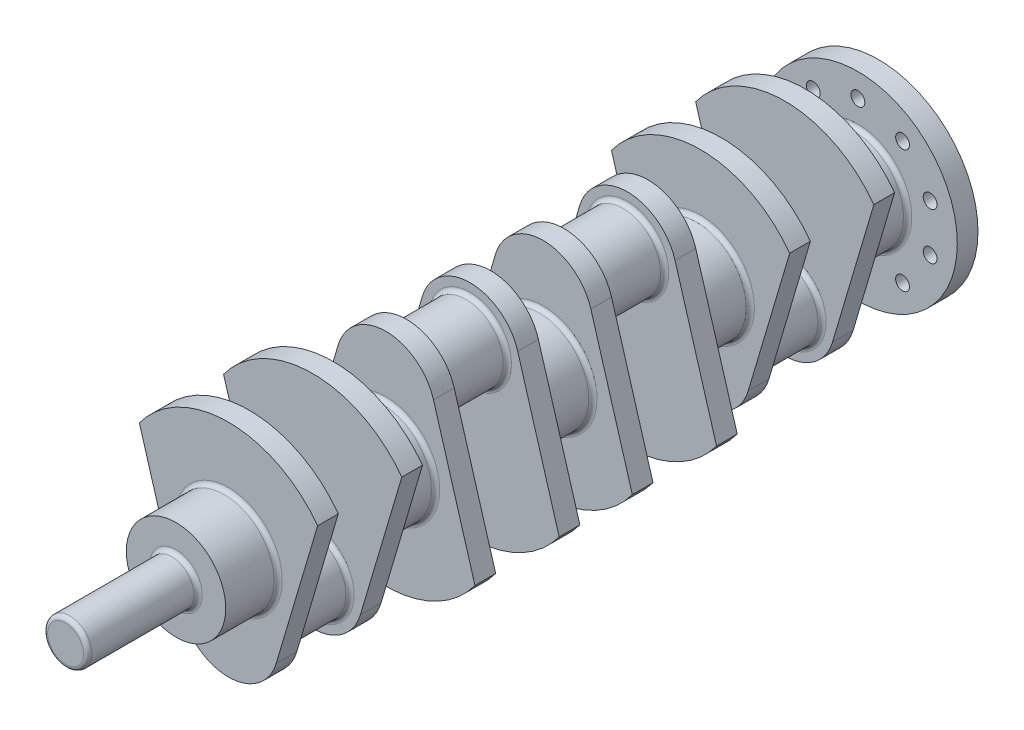
SolidWorks part; units mm, degrees
ref_plane "Front Plane" through (0, 0, 0) normal (0, 0, 1) x (1, 0, 0)
ref_plane "Top Plane" through (0, 0, 0) normal (0, 1, 0) x (1, 0, 0)
ref_plane "Right Plane" through (0, 0, 0) normal (1, 0, 0) x (0, 0, -1)
sketch "Sketch1" plane through (0, 0, 0) normal (0, 0, 1) x (1, 0, 0)
  line L0 (0, 48.3144) -> (0, -83.5014) construction
  line L1 (-46.5551, 0) -> (125.5904, 0) construction
  line L2 (-64.5699, 47.2306) -> (-34.5175, -54.2246)
  line L3 (64.5699, 47.2306) -> (34.5175, -54.2246)
  circle A0 centre (0, -44) radius 36
  arc A1 (-64.5699, 47.2306) -> (64.5699, 47.2306) centre (0, 0) cw
  dimension "D1" = 72
  dimension "D4" = 80
  dimension "D2" = 33
  dimension "D3" = 44
extrude "Boss-Extrude1" add sketch "Sketch1" along normal blind 15 contours A1 L2 A0 L3 | A0
sketch "Sketch2" plane through (0, 0, 15) normal (0, 0, 1) x (1, 0, 0)
  circle A1 centre (0, -44) radius 27
  dimension "D1" = 54
extrude "Boss-Extrude2" add sketch "Sketch2" along normal blind 46
sketch "Sketch3" plane through (0, 0, 0) normal (0, 0, -1) x (-1, 0, 0)
  circle A0 centre (0, 0) radius 36
  dimension "D1" = 72
extrude "Boss-Extrude3" add sketch "Sketch3" along normal blind 38
ref_plane "Plane1" through (0, 0, 38) normal (0, 0, 1) x (1, 0, 0)
mirror "Mirror1" about plane through (0, 0, 38) normal (0, 0, 1) of "Boss-Extrude1", "Boss-Extrude3"
ref_plane "Plane2" through (0, 0, 95) normal (0, 0, 1) x (1, 0, 0)
mirror "Mirror2" about plane through (0, 0, 95) normal (0, 0, 1) of bodies 104
move or copy body "Body-Move/Copy1" bodies to move or copy 105 copy no rotation origin (0, 0, 152) rotation axis (1, 0, 0) rotation angle 180
ref_plane "Plane3" through (0, 0, 209) normal (0, 0, 1) x (1, 0, 0)
mirror "Mirror3" about plane through (0, 0, 209) normal (0, 0, 1) of bodies 106 104
sketch "Sketch5" plane through (0, 0, 456) normal (0, 0, 1) x (1, 0, 0)
  circle A0 centre (0, 0) radius 16
  dimension "D1" = 32
extrude "Boss-Extrude4" add sketch "Sketch5" along normal blind 80
sketch "Sketch6" plane through (0, 0, -38) normal (0, 0, -1) x (-1, 0, 0)
  circle A0 centre (0, 0) radius 72
  dimension "D1" = 144
extrude "Boss-Extrude5" add sketch "Sketch6" along normal blind 15
sketch "Sketch7" plane through (0, 0, -53) normal (0, 0, -1) x (-1, 0, 0)
  line L0 (0, 0) -> (0, 55) construction
  circle A0 centre (0, 55) radius 5
  circle A1 centre (32.3282, 44.4959) radius 5
  circle A2 centre (52.3081, 16.9959) radius 5
  circle A3 centre (52.3081, -16.9959) radius 5
  circle A4 centre (32.3282, -44.4959) radius 5
  circle A5 centre (0, -55) radius 5
  circle A6 centre (-32.3282, -44.4959) radius 5
  circle A7 centre (-52.3081, -16.9959) radius 5
  circle A8 centre (-52.3081, 16.9959) radius 5
  circle A9 centre (-32.3282, 44.4959) radius 5
  dimension "D1" = 10
  dimension "D2" = 55
  dimension "D4" = 55
  dimension "D5" = 110
  dimension "D3" = 10
extrude "Cut-Extrude1" cut sketch "Sketch7" against normal up to next (15 mm away)
combine bodies "Combine1" operation type add bodies to combine 109 107 106 111
fillet "Fillet1" radius 3 19 edges at (-36, 0, 76) (-36, 0, -38) (27, -44, 15) (27, -44, 61) (-36, 0, 0) (-36, 0, 190) (27, 44, 129) (27, 44, 175) (-36, 0, 114) (-36, 0, 228) (27, 44, 289) (27, 44, 243) (-36, 0, 342) (-36, 0, 304) (27, -44, 403) (27, -44, 357) (-36, 0, 418) (16, 0, 456) (16, 0, 536)
